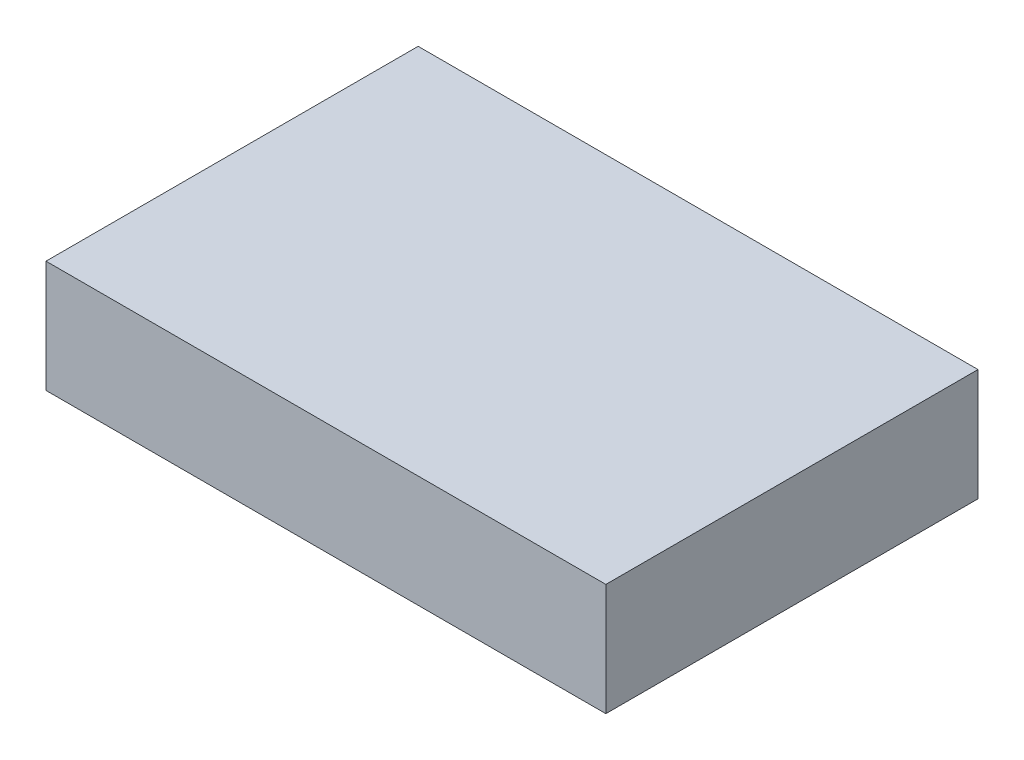
SolidWorks part; units mm, degrees
ref_plane "Front Plane" through (0, 0, 0) normal (0, 0, 1) x (1, 0, 0)
ref_plane "Top Plane" through (0, 0, 0) normal (0, 1, 0) x (1, 0, 0)
ref_plane "Right Plane" through (0, 0, 0) normal (1, 0, 0) x (0, 0, -1)
sketch "Sketch1" plane through (0, 0, 0) normal (0, 1, 0) x (1, 0, 0)
  line L1 (0, 0) -> (-85, 0)
  line L2 (0, 0) -> (0, -56.5)
  line L3 (0, -56.5) -> (-85, -56.5)
  line L4 (-85, 0) -> (-85, -56.5)
  dimension "D1" = 85
  dimension "D2" = 56.5
extrude "Boss-Extrude1" add sketch "Sketch1" along normal blind 17
equation "\"largo\"=8.5"
equation "\"D1@Sketch1\"=\"largo\""
equation "\"ancho\"=5.65"
equation "\"D2@Sketch1\"=\"ancho\""
equation "\"alto\"=1.7"
equation "\"D1@Boss-Extrude1\"=\"alto\""
